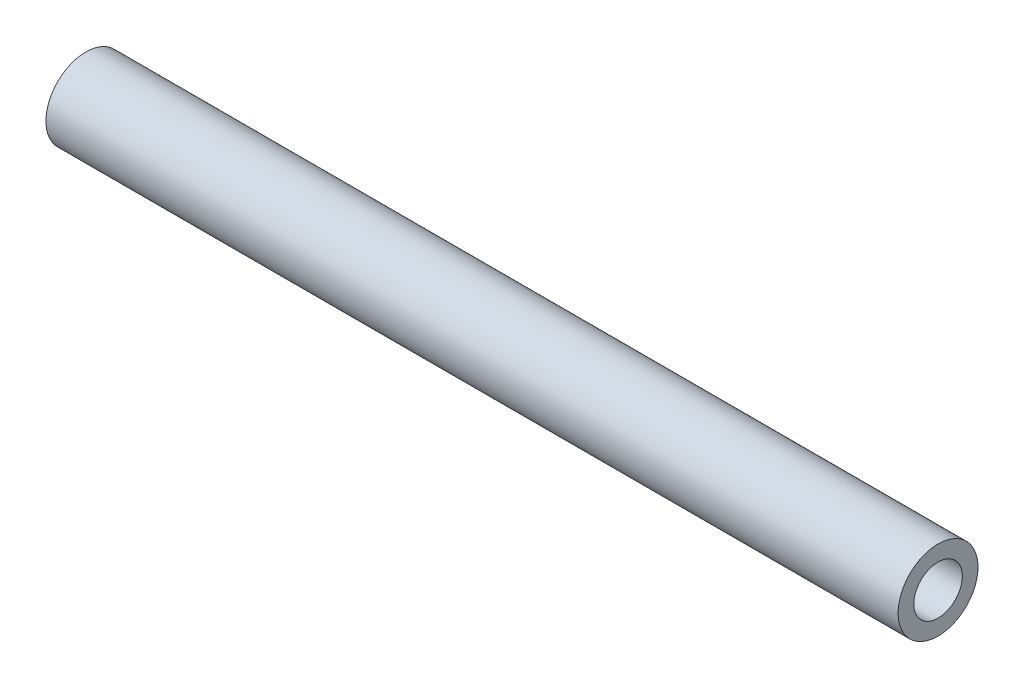
SolidWorks part; units mm, degrees
ref_plane "Front Plane" through (0, 0, 0) normal (0, 0, 1) x (1, 0, 0)
ref_plane "Top Plane" through (0, 0, 0) normal (0, 1, 0) x (1, 0, 0)
ref_plane "Right Plane" through (0, 0, 0) normal (1, 0, 0) x (0, 0, -1)
sketch "Sketch1" plane through (0, 0, 0) normal (1, 0, 0) x (0, 0, -1)
  circle A0 centre (0, 0) radius 4.7625
  circle A1 centre (0, 0) radius 2.8956
  dimension "D1" = 9.525
  dimension "D2" = 5.7912
extrude "Boss-Extrude1" add sketch "Sketch1" along normal blind 101.6
